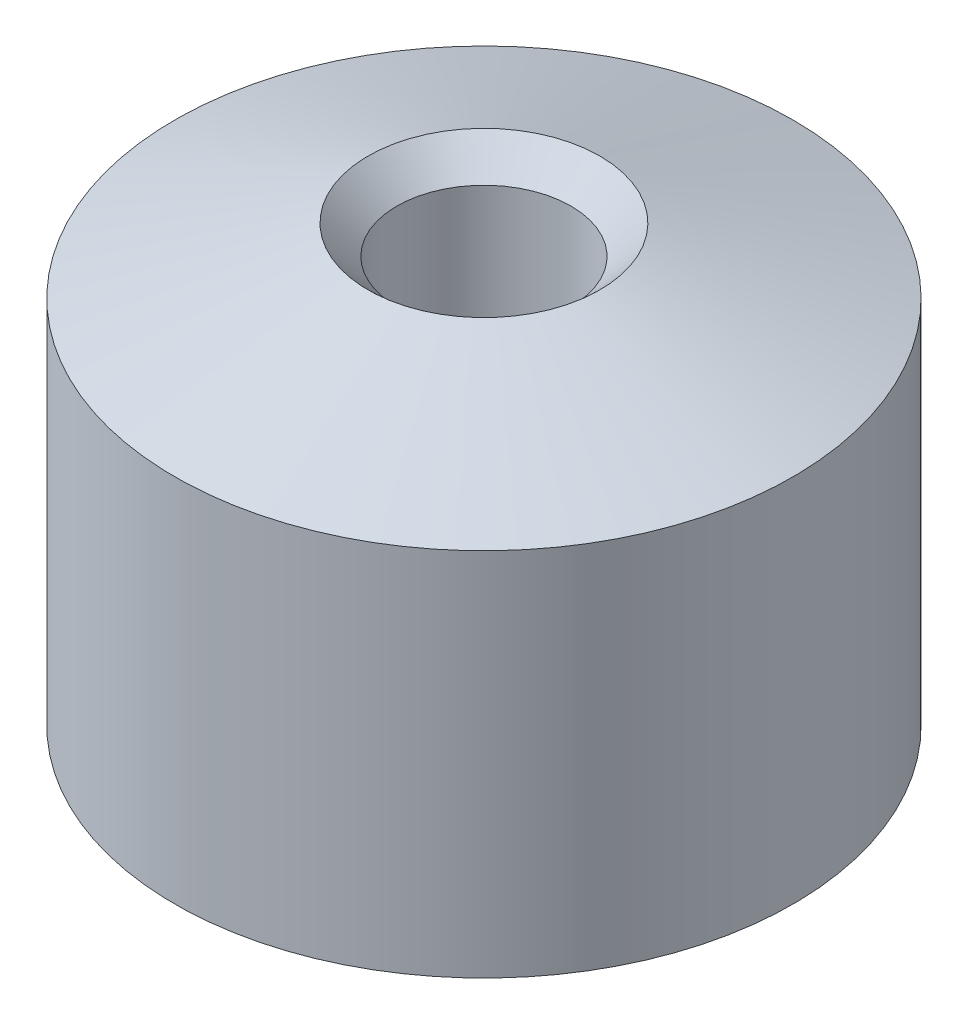
SolidWorks part; units mm, degrees
ref_plane "Front Plane" through (0, 0, 0) normal (0, 0, 1) x (1, 0, 0)
ref_plane "Top Plane" through (0, 0, 0) normal (0, 1, 0) x (1, 0, 0)
ref_plane "Right Plane" through (0, 0, 0) normal (1, 0, 0) x (0, 0, -1)
sketch "Sketch2" plane through (0, 0, 0) normal (0, 0, 1) x (1, 0, 0)
  line L1 (-14.2, 18.5) -> (-4, 18.5)
  line L2 (-14.2, 18.5) -> (-14.2, 35.5)
  line L3 (-4, 37.1734) -> (-5.3266, 38.5)
  line L4 (-14.2, 35.5) -> (-5.3266, 38.5)
  line L7 (-4, 18.5) -> (-4, 37.1734)
  line L11 (0, 15.2) -> (0, 41.79) construction
  line L12 (74.5, 15.2) -> (-74.5, 15.2) construction
  dimension "D2" = 17
revolve "Revolve1" add sketch "Sketch2" angle 360 about L11
